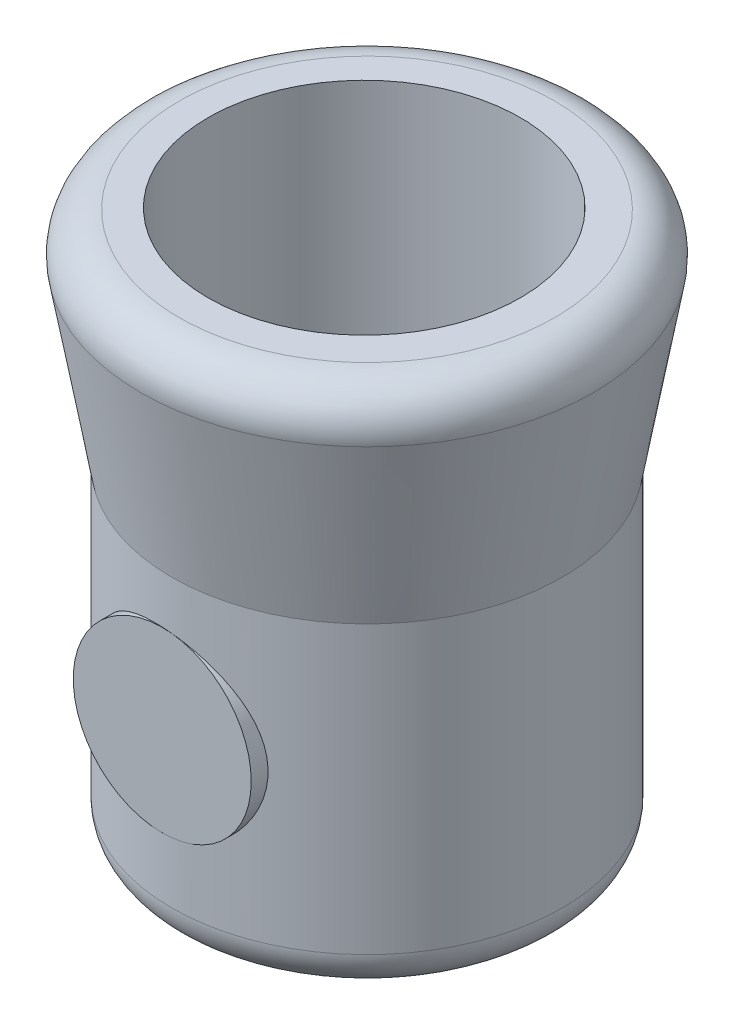
SolidWorks part; units mm, degrees
ref_plane "Front Plane" through (0, 0, 0) normal (0, 0, 1) x (1, 0, 0)
ref_plane "Top Plane" through (0, 0, 0) normal (0, 1, 0) x (1, 0, 0)
ref_plane "Right Plane" through (0, 0, 0) normal (1, 0, 0) x (0, 0, -1)
sketch "Sketch12" plane through (0, 0, 0) normal (0, 0, 1) x (1, 0, 0)
  line L0 (1.0362, -5.8693) -> (5, -28.3217)
  line L1 (5, -28.3217) -> (5, -65)
  line L2 (10, -70) -> (30, -70)
  line L3 (30, -70) -> (30, 0)
  line L4 (30, 0) -> (5.96, 0)
  arc A0 (1.0362, -5.8693) -> (5.96, 0) centre (5.96, -5) cw
  arc A1 (10, -70) -> (5, -65) centre (10, -65) cw
  point P8 (0, 0)
  point P11 (5, -70)
  dimension "D4" = 5
  dimension "D5" = 5
  dimension "D1" = 70
  dimension "D2" = 25
  dimension "D3" = 30
revolve "Revolve2" add sketch "Sketch12" angle 360 about L3
sketch "Sketch13" plane through (0, 0, 0) normal (0, 1, 0) x (1, 0, 0)
  circle A0 centre (29.6447, 0) radius 20
  dimension "D1" = 40
extrude "Cut-Extrude1" cut sketch "Sketch13" against normal blind 29
sketch "Sketch14" plane through (0, 0, 0) normal (0, 0, 1) x (1, 0, 0)
  circle A0 centre (28.7724, -45.8771) radius 11.3974
extrude "Boss-Extrude1" add sketch "Sketch14" along normal blind 25
